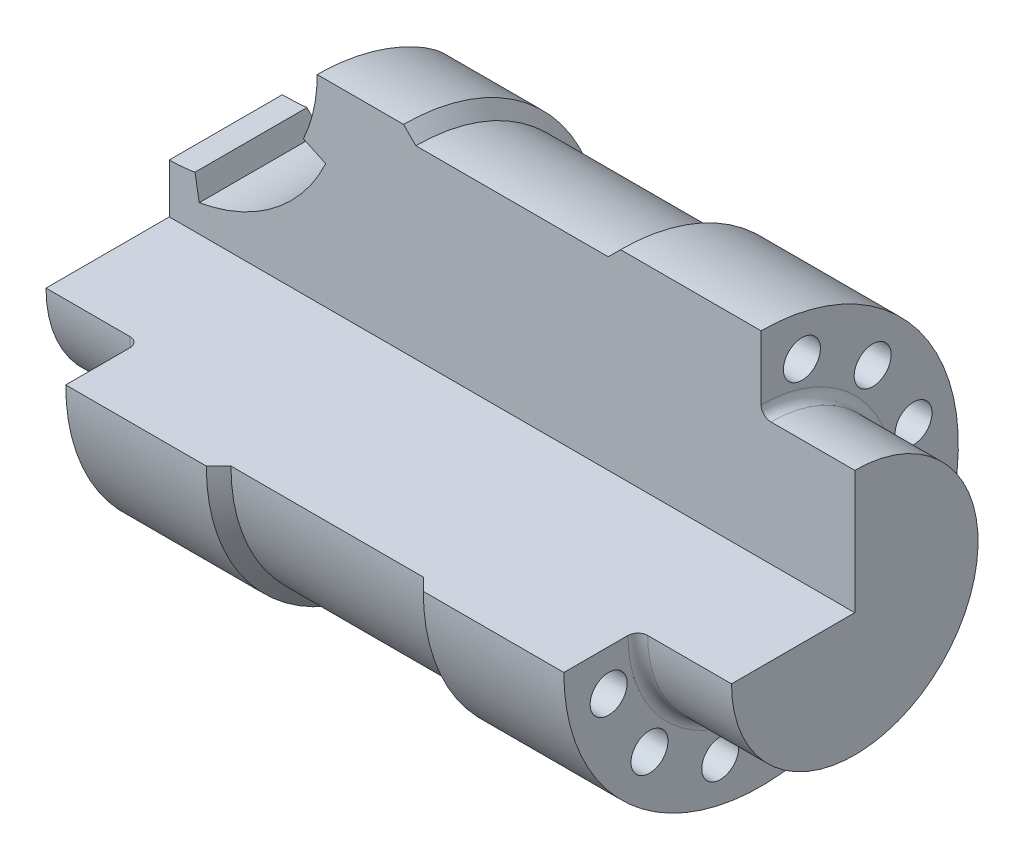
SolidWorks part; units mm, degrees
ref_plane "Front Plane" through (0, 0, 0) normal (0, 0, 1) x (1, 0, 0)
ref_plane "Top Plane" through (0, 0, 0) normal (0, 1, 0) x (1, 0, 0)
ref_plane "Right Plane" through (0, 0, 0) normal (1, 0, 0) x (0, 0, -1)
sketch "Sketch1" plane through (0, 0, 0) normal (0, 1, 0) x (1, 0, 0)
  line L0 (0, 0) -> (139, 0)
  line L1 (139, 0) -> (139, 25)
  line L2 (139, 25) -> (120, 25)
  line L3 (120, 25) -> (120, 40)
  line L4 (120, 40) -> (91.5, 40)
  line L5 (91.5, 40) -> (89, 37.5)
  line L6 (89, 37.5) -> (50, 37.5)
  line L7 (50, 37.5) -> (47.5, 40)
  line L8 (47.5, 40) -> (19, 40)
  line L9 (19, 40) -> (19, 25)
  line L10 (19, 25) -> (0, 25)
  line L11 (0, 25) -> (0, 0)
  point P13 (0, 0)
  point P14 (0, 0)
  dimension "D1" = 139
  dimension "D2" = 19
  dimension "D3" = 19
  dimension "D4" = 28.5
  dimension "D5" = 28.5
  dimension "D6" = 45
  dimension "D7" = 2.5
  dimension "D8" = 25
  dimension "D9" = 40
revolve "Revolve1" add sketch "Sketch1" angle 360 about L0
sketch "Sketch2" plane through (120, 0, 0) normal (1, 0, 0) x (0, 0, -1)
  line L0 (0, 0) -> (0, 40) construction
  line L1 (0, 0) -> (-8.2822, 30.9096)
  circle A0 centre (0, 0) radius 32 construction
  circle A1 centre (0, 0) radius 40 construction
  circle A2 centre (-8.2822, 30.9096) radius 3.75
  circle A3 centre (8.2822, 30.9096) radius 3.75
  circle A4 centre (22.6274, 22.6274) radius 3.75
  circle A5 centre (30.9096, 8.2822) radius 3.75
  circle A6 centre (30.9096, -8.2822) radius 3.75
  circle A7 centre (22.6274, -22.6274) radius 3.75
  circle A8 centre (8.2822, -30.9096) radius 3.75
  circle A9 centre (-8.2822, -30.9096) radius 3.75
  circle A10 centre (-22.6274, -22.6274) radius 3.75
  circle A11 centre (-30.9096, -8.2822) radius 3.75
  circle A12 centre (-30.9096, 8.2822) radius 3.75
  circle A13 centre (-22.6274, 22.6274) radius 3.75
  point P9 (0, 0)
  point P10 (0, 0)
  point P11 (0, 0)
  point P34 (0, 0)
  point P35 (0, 0)
  point P36 (0, 0)
  point P37 (0, 0)
  point P38 (0, 0)
  point P39 (0, 0)
  dimension "D1" = 64
  dimension "D3" = 7.5
  dimension "D2" = 15
  dimension "D4" = 12
extrude "Cut-Extrude1" cut sketch "Sketch2" against normal through all
fillet "Fillet1" radius 2 2 edges at (120, 0, 25) (19, 0, 25)
sketch "Sketch3" plane through (0, 0, 0) normal (-1, 0, 0) x (0, 0, 1)
  line L0 (0, 0) -> (0, 40)
  line L1 (0, 0) -> (40, 0)
  circle A0 centre (0, 0) radius 40 construction
  arc A1 (40, 0) -> (0, 40) centre (0, 0) ccw
extrude "Cut-Extrude2" cut sketch "Sketch3" against normal through all
sketch "Sketch5" plane through (0, 0, 0) normal (0, 0, 1) x (1, 0, 0)
  line L0 (0, 0) -> (0, 40)
  line L1 (0, 40) -> (30, 40)
  line L3 (0, 40) -> (6.0777, 5.5317)
  line L4 (0, 40) -> (31.7208, 25.2084)
  arc A0 (27.1892, 27.3215) -> (30, 40) centre (0, 40) ccw
  arc A1 (6.0777, 5.5317) -> (31.7208, 25.2084) centre (0, 40) ccw
  arc A2 (0, 10) -> (5.2094, 10.4558) centre (0, 40) ccw
  line M7 (47.5, 40) -> (19, 40)
  line M8 (19, 40) -> (19, 27)
  arc M9 (19, 27) -> (17, 25) centre (17, 27) cw
  line M10 (17, 25) -> (0, 25)
  line M11 (0, 25) -> (0, 0)
  dimension "D2" = 60
  dimension "D3" = 70
  dimension "D1" = 40
  dimension "D4" = 10
  dimension "D5" = 25
extrude "Cut-Extrude3" cut sketch "Sketch5" against normal through all contours L3 A1 L4 M8 M9 M10 | L4 A0 M7 M8 | A2 L3 M11 M10
equation "\"a\"= 139"
equation "\"b\"= 19"
equation "\"c\"= 28.5"
